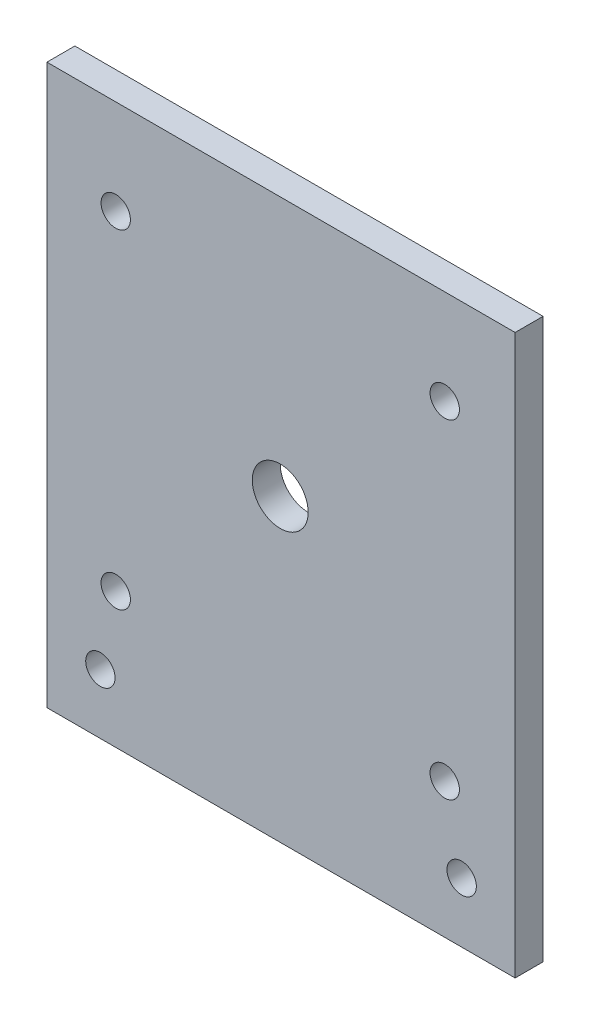
SolidWorks part; units mm, degrees
ref_plane "Plan de face" through (0, 0, 0) normal (0, 0, 1) x (1, 0, 0)
ref_plane "Plan de dessus" through (0, 0, 0) normal (0, 1, 0) x (1, 0, 0)
ref_plane "Plan de droite" through (0, 0, 0) normal (1, 0, 0) x (0, 0, -1)
sketch "Esquisse1" plane through (0, 0, 0) normal (0, 0, 1) x (1, 0, 0)
  line L1 (32.5, -40) -> (-32.5, -40)
  line L2 (32.5, -40) -> (32.5, 40)
  line L3 (32.5, 40) -> (-32.5, 40)
  line L4 (-32.5, -40) -> (-32.5, 40)
  line L5 (32.5, -40) -> (-32.5, 40) construction
  line L6 (32.5, 40) -> (-32.5, -40) construction
  point P0 (0, 0)
  dimension "D1" = 65
  dimension "D2" = 80
extrude "Boss.-Extru.1" add sketch "Esquisse1" along normal blind 4
sketch "Esquisse2" plane through (0, 0, 0) normal (0, 0, -1) x (-1, 0, 0)
  line L0 (0, 0) -> (0, -40) construction
  line L1 (32.5, -40) -> (-32.5, -40) construction
  circle A0 centre (25.85, -31.439) radius 2.1
  circle A1 centre (-25.85, -31.439) radius 2.1
  dimension "D1" = 4.2
  dimension "D2" = 25.85
  dimension "D3" = 8.561
extrude "Enlèv. mat.-Extru.1" cut sketch "Esquisse2" against normal through all
sketch "Esquisse3" plane through (0, 0, 4) normal (0, 0, 1) x (1, 0, 0)
  line L0 (-32.5, 40) -> (-32.5, -40) construction
  line L1 (23.4266, -20.64) -> (-23.6534, -20.64) construction
  line L2 (23.4266, -20.64) -> (23.4266, 26.44) construction
  line L3 (23.4266, 26.44) -> (-23.6534, 26.44) construction
  line L4 (-23.6534, -20.64) -> (-23.6534, 26.44) construction
  line L5 (32.5, 40) -> (-32.5, 40) construction
  line L6 (23.4266, -20.64) -> (-23.6534, 26.44) construction
  circle A0 centre (-23.6534, -20.64) radius 2.1
  circle A1 centre (23.4266, -20.64) radius 2.1
  circle A2 centre (23.4266, 26.44) radius 2.1
  circle A3 centre (-23.6534, 26.44) radius 2.1
  circle A4 centre (-0.1134, 2.9) radius 4
  dimension "D1" = 4.2
  dimension "D2" = 8
  dimension "D3" = 47.08
  dimension "D4" = 8.8466
  dimension "D5" = 13.56
extrude "Enlèv. mat.-Extru.2" cut sketch "Esquisse3" against normal through all
sketch "Esquisse4" plane through (0, 0, 0) normal (0, 0, -1) x (-1, 0, 0)
  line L0 (-32.5, 40) -> (32.5, 40) construction
  line L1 (32.5, -40) -> (33.5, -40)
  line L2 (32.5, -40) -> (32.5, 40)
  line L3 (32.5, 40) -> (33.5, 40)
  line L4 (33.5, -40) -> (33.5, 40)
  line L5 (0, -40) -> (0, 40) construction
  line L6 (32.5, -40) -> (-32.5, -40) construction
  line L7 (-33.5, -40) -> (-33.5, 40)
  line L8 (-32.5, 40) -> (-33.5, 40)
  line L9 (-32.5, -40) -> (-32.5, 40)
  line L10 (-32.5, -40) -> (-33.5, -40)
  dimension "D1" = 1
extrude "Boss.-Extru.2" add sketch "Esquisse4" against normal blind 4
